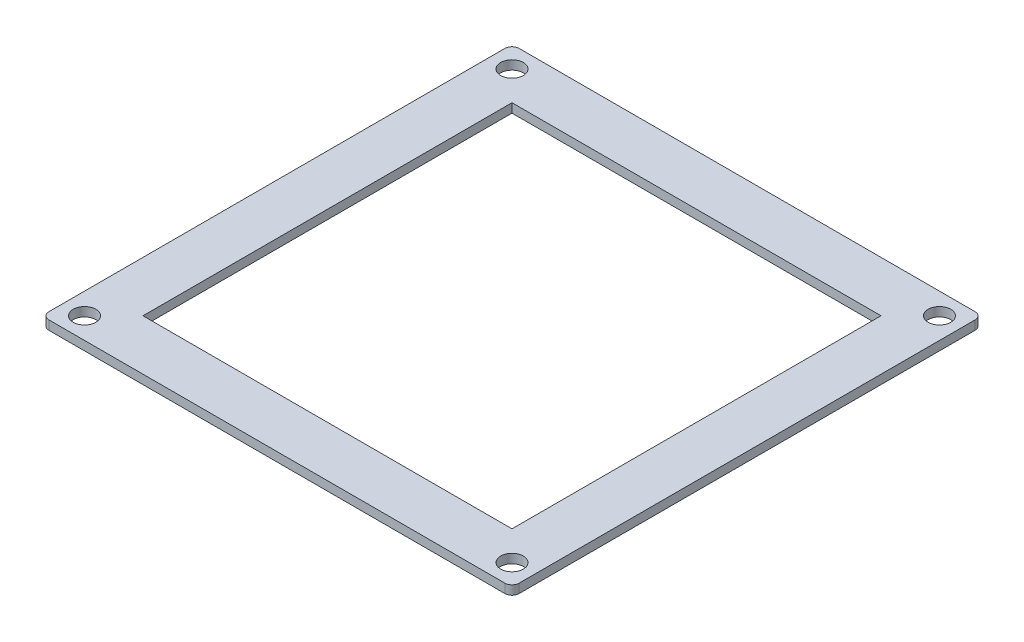
SolidWorks part; units mm, degrees
ref_plane "Front Plane" through (0, 0, 0) normal (0, 0, 1) x (1, 0, 0)
ref_plane "Top Plane" through (0, 0, 0) normal (0, 1, 0) x (1, 0, 0)
ref_plane "Right Plane" through (0, 0, 0) normal (1, 0, 0) x (0, 0, -1)
sketch "Sketch1" plane through (0, 0, 0) normal (0, 1, 0) x (1, 0, 0)
  line L1 (-30, 30) -> (30, 30) construction
  line L2 (-30, 30) -> (-30, -30) construction
  line L3 (-30, -30) -> (30, -30) construction
  line L4 (30, 30) -> (30, -30) construction
  line L5 (0, -30) -> (0, 30) construction
  line L6 (-30, 0) -> (30, 0) construction
  line L7 (-25.9, 25.9) -> (25.9, 25.9)
  line L8 (-25.9, 25.9) -> (-25.9, -25.9)
  line L9 (-25.9, -25.9) -> (25.9, -25.9)
  line L10 (25.9, 25.9) -> (25.9, -25.9)
  line L11 (0, -25.9) -> (0, 25.9) construction
  line L12 (-25.9, 0) -> (25.9, 0) construction
  line L13 (-33, 33) -> (33, 33)
  line L14 (-33, 33) -> (-33, -33)
  line L15 (-33, -33) -> (33, -33)
  line L16 (33, 33) -> (33, -33)
  line L17 (0, -33) -> (0, 33) construction
  line L18 (-33, 0) -> (33, 0) construction
  circle A0 centre (-30, 30) radius 1.59
  circle A1 centre (30, 30) radius 1.59
  circle A2 centre (30, -30) radius 1.59
  circle A3 centre (-30, -30) radius 1.59
  point P0 (0, 0)
  point P9 (0, 0)
  point P13 (0, 0)
  dimension "D1" = 3.18
  dimension "D2" = 60
  dimension "D3" = 51.8
  dimension "D4" = 3
  dimension "D5" = 3
  dimension "D6" = 66
extrude "Boss-Extrude1" add sketch "Sketch1" along normal blind 1.27
fillet "Fillet1" radius 1 4 edges at (33, 0.635, 33) (-33, 0.635, 33) (-33, 0.635, -33) (33, 0.635, -33)
equation "\"Lens_dim\"= 50.8"
equation "\"D3@Sketch1\"=\"Lens_dim\" +0.5*2"
equation "\"D5@Sketch1\"=\"D4@Sketch1\""
